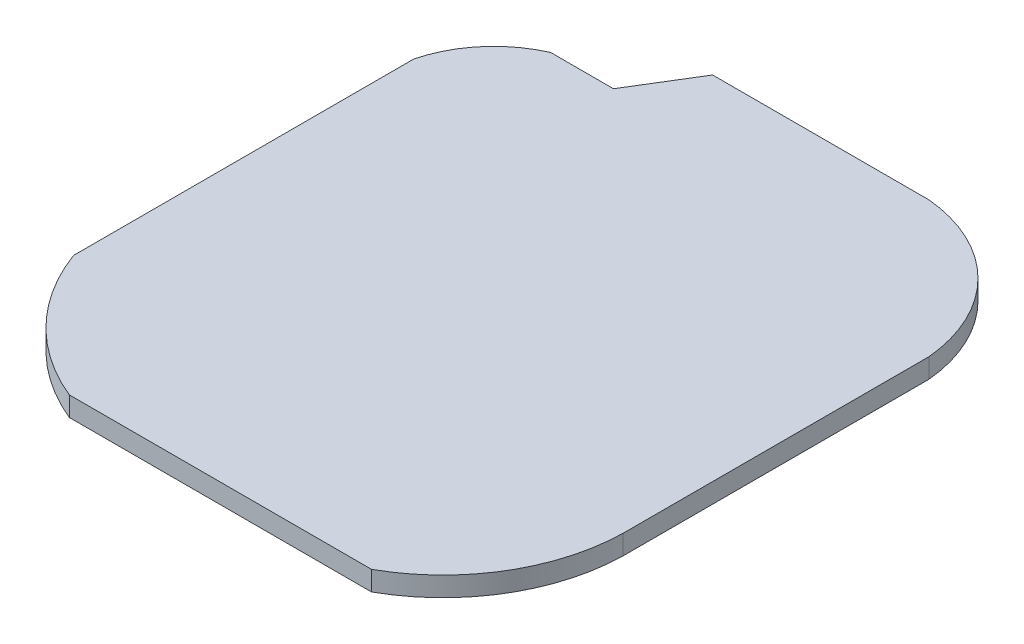
SolidWorks part; units mm, degrees
ref_plane "Front Plane" through (0, 0, 0) normal (0, 0, 1) x (1, 0, 0)
ref_plane "Top Plane" through (0, 0, 0) normal (0, 1, 0) x (1, 0, 0)
ref_plane "Right Plane" through (0, 0, 0) normal (1, 0, 0) x (0, 0, -1)
sketch "Sketch3" plane through (0, 0, 0) normal (0, 1, 0) x (1, 0, 0)
  line L1 (-131.4, -152.64) -> (131.4, -152.64)
  line L2 (-131.4, -152.64) -> (-131.4, 152.64)
  line L3 (-131.4, 152.64) -> (131.4, 152.64)
  line L4 (131.4, -152.64) -> (131.4, 152.64)
  line L5 (-131.4, -152.64) -> (131.4, 152.64) construction
  line L6 (-131.4, 152.64) -> (131.4, -152.64) construction
  point P0 (0, 0)
extrude "Boss-Extrude3" add sketch "Sketch3" along normal blind 10
sketch "Sketch4" plane through (0, 10, 0) normal (0, 1, 0) x (1, 0, 0)
  line L0 (0, 0) -> (0, 36) construction
  line L1 (-131.4, -152.64) -> (-131.4, -90) construction
  line L2 (-131.4, 152.64) -> (-131.4, -152.64) construction
  line L3 (-131.4, -152.64) -> (-70.92, -152.64) construction
  line L4 (-131.4, -152.64) -> (131.4, -152.64) construction
  line L5 (-131.4, -90) -> (-131.4, -152.64)
  line L6 (-131.4, -152.64) -> (-70.92, -152.64)
  line L7 (131.4, -152.64) -> (131.4, -72.72) construction
  line L8 (131.4, -152.64) -> (131.4, 152.64) construction
  line L9 (-131.4, -152.64) -> (83.16, -152.64) construction
  line L10 (83.16, -152.64) -> (131.4, -152.64)
  line L11 (131.4, -152.64) -> (131.4, -72.72)
  line L12 (131.4, -152.64) -> (131.4, 83.52) construction
  line L13 (-131.4, 152.64) -> (-131.4, 121.2871) construction
  line L14 (-99.3727, 121.2871) -> (-67.3455, 121.2871)
  line L15 (131.4, 83.52) -> (131.4, 152.64)
  line L16 (131.4, 152.64) -> (62.28, 152.64)
  line L17 (-131.4, 152.64) -> (-78.12, 152.64) construction
  line L18 (-131.4, 121.2871) -> (-67.3455, 121.2871) construction
  line L19 (-67.3455, 121.2871) -> (-48.1593, 152.64) construction
  line L20 (131.4, 152.64) -> (-131.4, 152.64) construction
  line L21 (131.4, 83.52) -> (-131.4, 83.52) construction
  line L22 (-67.3455, 121.2871) -> (-48.1593, 152.64)
  line L23 (-48.1593, 152.64) -> (-131.4, 152.64)
  line L24 (-131.4, 152.64) -> (-131.4, 83.52)
  arc A0 (-70.92, -152.64) -> (-131.4, -90) centre (-30.0903, -52.7009) cw
  arc A1 (83.16, -152.64) -> (131.4, -72.72) centre (37.7004, -70.6815) ccw
  arc A2 (62.28, 152.64) -> (131.4, 83.52) centre (55.08, 76.32) cw
  arc A3 (-131.4, 83.52) -> (-99.3727, 121.2871) centre (-76.5887, 69.5023) cw
extrude "Cut-Extrude1" cut sketch "Sketch4" against normal through all both and the other way through all
